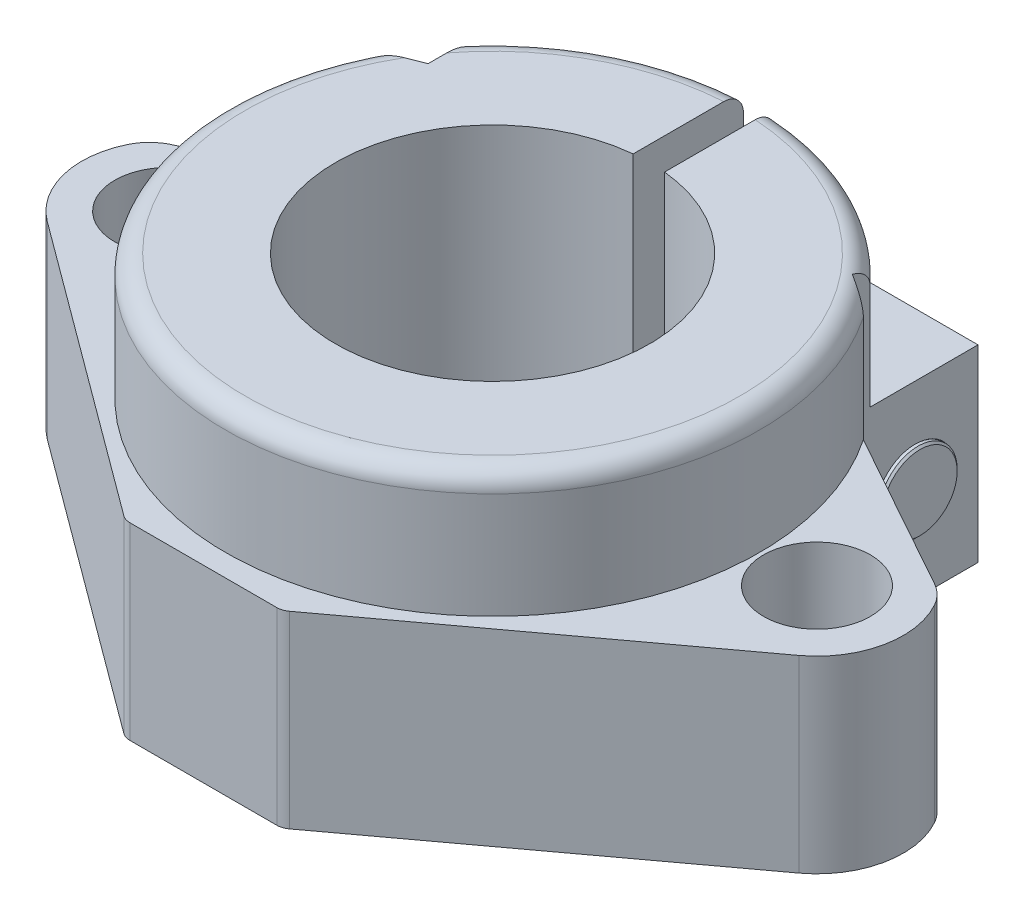
SolidWorks part; units mm, degrees
other "Markup1"
sketch "Sketch30" plane through (-28, 20, 19) normal (-0.8662, 0.4948, 0.0704) x (0.294, 0.3906, 0.8723)
ref_plane "Front Plane" through (0, 0, 0) normal (0, 0, 1) x (1, 0, 0)
ref_plane "Top Plane" through (0, 0, 0) normal (0, 1, 0) x (1, 0, 0)
ref_plane "Right Plane" through (0, 0, 0) normal (1, 0, 0) x (0, 0, -1)
sketch "Sketch1" plane through (0, 0, 0) normal (0, 1, 0) x (1, 0, 0)
  line L0 (0, 23.9567) -> (0, -22.6932) construction
  line L1 (-26.4411, 0) -> (25.427, 0) construction
  line L2 (5, -18.4) -> (-5, -18.4)
  line L3 (12.5, 18.4) -> (-12.5, 18.4)
  line L4 (-12.5, 18.4) -> (-24.8786, 3.517)
  line L5 (-5, -18.4) -> (-23.9181, -4.4237)
  line L6 (5, -18.4) -> (23.9181, -4.4237)
  line L7 (12.5, 18.4) -> (24.8786, 3.517)
  circle A1 centre (0, 0) radius 10 construction
  circle A2 centre (-20.65, 0) radius 3.4
  arc A3 (-24.8786, 3.517) -> (-23.9181, -4.4237) centre (-20.65, 0) ccw
  circle A4 centre (20.65, 0) radius 3.4
  arc A5 (24.8786, 3.517) -> (23.9181, -4.4237) centre (20.65, 0) cw
  point P20 (0, -18.4)
  point P21 (0, 18.4)
  dimension "D1" = 20
  dimension "D2" = 6.8
  dimension "D4" = 11
  dimension "D3" = 41.3
  dimension "D5" = 25
  dimension "D6" = 10
  dimension "D7" = 18.4
  dimension "D8" = 18.4
extrude "Boss-Extrude1" add sketch "Sketch1" along normal blind 12
sketch "Sketch3" plane through (0, 12, 0) normal (0, 1, 0) x (1, 0, 0)
  circle A0 centre (0, 0) radius 17
  dimension "D1" = 34
extrude "Boss-Extrude2" add sketch "Sketch3" along normal blind 8
fillet "Fillet1" radius 1.25 1 edges at (0, 20, 17)
sketch "Sketch2" plane through (0, 12, 0) normal (0, 1, 0) x (1, 0, 0)
  line L0 (12.5, 18.4) -> (12.5, 10.4)
  line L1 (12.5, 10.4) -> (24.8786, 3.517)
  line L2 (24.8786, 3.517) -> (12.5, 18.4)
  line L3 (-12.5, 18.4) -> (-12.5, 8.3996)
  line L4 (-12.5, 8.3996) -> (-24.8786, 3.517)
  line L5 (-24.8786, 3.517) -> (-12.5, 18.4)
  dimension "D1" = 8
  dimension "D2" = 10.0004
extrude "Cut-Extrude1" cut sketch "Sketch2" against normal through all both and the other way through all
sketch "Sketch4" plane through (0, 20, 0) normal (0, 1, 0) x (1, 0, 0)
  circle A0 centre (0, 0) radius 10
  dimension "D1" = 20
extrude "Cut-Extrude2" cut sketch "Sketch4" against normal through all both and the other way through all
sketch "Sketch5" plane through (0, 20, 0) normal (0, 1, 0) x (1, 0, 0)
  line L0 (0, 21.2575) -> (0, -21.4313) construction
  line L2 (1, 0) -> (-1, 0)
  line L3 (1, 0) -> (1, 20)
  line L4 (1, 20) -> (-1, 20)
  line L5 (-1, 0) -> (-1, 20)
  line L6 (1, 0) -> (-1, 20) construction
  line L7 (1, 20) -> (-1, 0) construction
  circle A0 centre (0, 0) radius 10 construction
  point P3 (0, 10)
  dimension "D1" = 2
  dimension "D2" = 20
extrude "Cut-Extrude3" cut sketch "Sketch5" against normal through all both
sketch "Sketch7" plane through (-12.5, 0, 0) normal (-1, 0, 0) x (0, 0, 1)
  line L0 (-8.3996, 0) -> (-18.4, 0) construction
  line L1 (-18.4, 12) -> (-18.4, 0) construction
  circle A0 centre (-14.4, 6) radius 3
  dimension "D1" = 6
  dimension "D2" = 6
  dimension "D3" = 4
extrude "Cut-Extrude4" cut sketch "Sketch7" against normal blind 12.5
fillet "Fillet2" radius 3 2 edges at (-24.8786, 6, -3.517) (24.8786, 6, -3.517)
fillet "Fillet3" radius 1 2 edges at (-5, 6, 18.4) (5, 6, 18.4)
hole_wizard "M5 Tapped Hole2" positions "Sketch15" profile "Sketch16" tap size "M5" standard "ISO" end condition through all
sketch "Sketch15" plane through (12.5, 0, 0) normal (1, 0, 0) x (0, 0, -1)
  line L0 (18.4, 12) -> (18.4, 0) construction
  line L1 (18.4, 0) -> (10.4, 0) construction
  point P0 (14.4, 6)
  dimension "D1" = 4
  dimension "D2" = 6
sketch "Sketch16" plane through (12.5, 6, -14.4) normal (0, 1, 0) x (0, 0, -1)
  line L0 (0, 0) -> (0, 38.65)
  line L1 (0, 38.65) -> (2.1, 38.65)
  line L2 (2.1, 38.65) -> (2.1, 0.425)
  line L3 (2.1, 0.425) -> (2.525, 0)
  line L5 (2.525, 0) -> (0, 0)
  line L6 (-2.1, 0.425) -> (-2.525, 0) construction
  line L11 (0, -6.35) -> (0, 107.95) construction
  dimension "Thru Tap Drill Dia." = 4.2
  dimension "Thru Tap Drill Depth" = 38.65
  dimension "Near C'Sink Dia." = 5.05
  dimension "Near C'Sink Angle" = 90
cosmetic thread "Hole Thread2" parameters "D2"=5
ref_plane "Plane3" through (-12.7, 0, 0) normal (-1, 0, 0) x (0, 0, 1)
sketch "Sketch26" plane through (-12.7, 0, 0) normal (-1, 0, 0) x (0, 0, 1)
  circle A0 centre (-14.4, 6) radius 2.5
  dimension "D1" = 5
extrude "Boss-Extrude4" add sketch "Sketch26" along normal blind 0.001 and the other way blind 25.5 separate body
sketch "Sketch28" plane through (-12.701, 0, 0) normal (-1, 0, 0) x (0, 0, 1)
  circle A0 centre (-14.4, 6) radius 4
  dimension "D1" = 8
extrude "Boss-Extrude5" add sketch "Sketch28" along normal blind 5
chamfer "Chamfer1" distance 0.125 angle 45 1 edges at (12.8, 6, -11.9)
sketch "Sketch29" plane through (-17.701, 0, 0) normal (-1, 0, 0) x (0, 0, 1)
  line L1 (-15.0678, 8.5705) -> (-16.96, 6.7069)
  line L2 (-16.96, 6.7069) -> (-16.2922, 4.1364)
  line L3 (-16.2922, 4.1364) -> (-13.7322, 3.4295)
  line L4 (-13.7322, 3.4295) -> (-11.84, 5.2931)
  line L5 (-11.84, 5.2931) -> (-12.5078, 7.8636)
  line L6 (-12.5078, 7.8636) -> (-15.0678, 8.5705)
  circle A0 centre (-14.4, 6) radius 2.3 construction
extrude "Cut-Extrude5" cut sketch "Sketch29" against normal blind 3
fillet "Fillet4" radius 0.75 1 edges at (-17.701, 6, -10.4)
